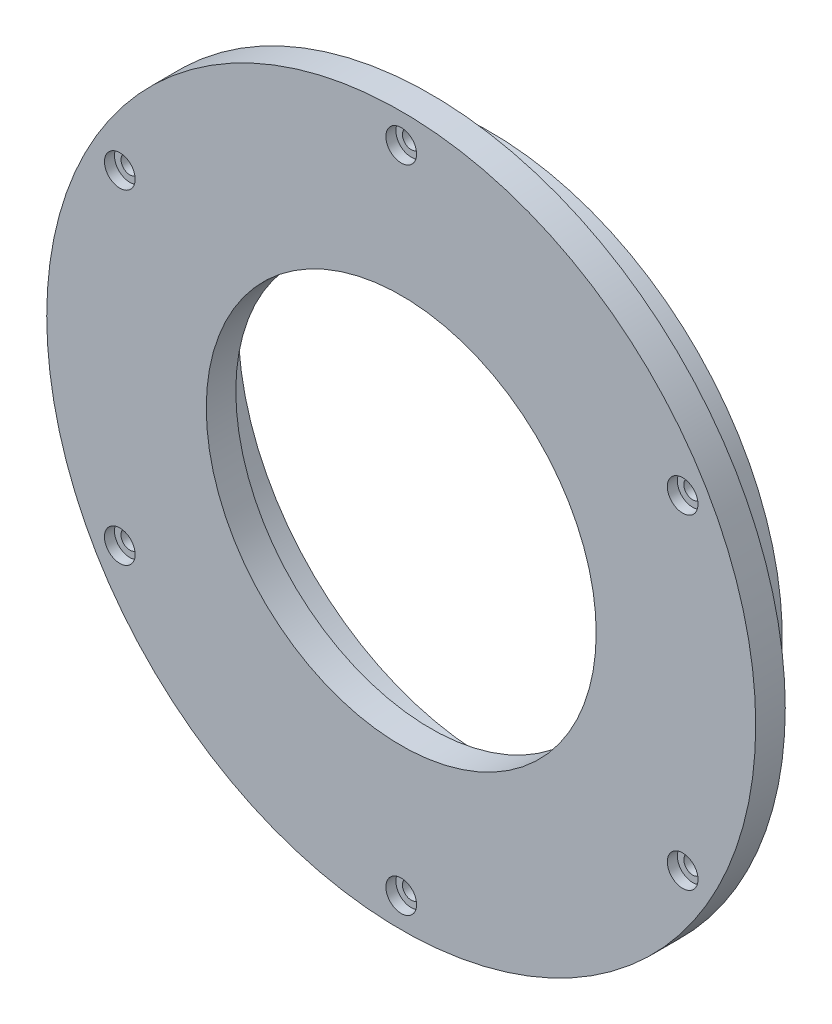
SolidWorks part; units mm, degrees
ref_plane "Front Plane" through (0, 0, 0) normal (0, 0, 1) x (1, 0, 0)
ref_plane "Top Plane" through (0, 0, 0) normal (0, 1, 0) x (1, 0, 0)
ref_plane "Right Plane" through (0, 0, 0) normal (1, 0, 0) x (0, 0, -1)
sketch "Sketch1" plane through (0, 0, 0) normal (0, 0, 1) x (1, 0, 0)
  circle A0 centre (0, 0) radius 60
  circle A1 centre (0, 0) radius 33
  dimension "D1" = 120
  dimension "D2" = 66
extrude "Boss-Extrude1" add sketch "Sketch1" along normal blind 5
sketch "Sketch2" plane through (0, 0, 0) normal (0, 0, -1) x (-1, 0, 0)
  circle A0 centre (0, 0) radius 49.5
  circle A1 centre (0, 0) radius 42.6
  dimension "D1" = 99
  dimension "D2" = 85.2
extrude "Boss-Extrude2" add sketch "Sketch2" along normal blind 10
sketch "Sketch3" plane through (0, 0, -10) normal (0, 0, -1) x (-1, 0, 0)
  circle A0 centre (0, 45) radius 1.7
  circle A1 centre (5.53, 44.6589) radius 1.7
  circle A2 centre (10.9761, 43.6409) radius 1.7
  circle A3 centre (16.2559, 41.9613) radius 1.7
  circle A4 centre (21.2892, 39.6455) radius 1.7
  circle A5 centre (25.9998, 36.7289) radius 1.7
  circle A6 centre (30.3163, 33.2554) radius 1.7
  circle A7 centre (34.1732, 29.2778) radius 1.7
  circle A8 centre (37.5121, 24.8564) radius 1.7
  circle A9 centre (40.2823, 20.0582) radius 1.7
  circle A10 centre (42.4419, 14.956) radius 1.7
  circle A11 centre (43.9582, 9.627) radius 1.7
  circle A12 centre (44.808, 4.1521) radius 1.7
  circle A13 centre (44.9787, -1.3858) radius 1.7
  circle A14 centre (44.4674, -6.9026) radius 1.7
  circle A15 centre (43.2822, -12.3148) radius 1.7
  circle A16 centre (41.4407, -17.5404) radius 1.7
  circle A17 centre (38.9711, -22.5) radius 1.7
  circle A18 centre (35.9108, -27.1186) radius 1.7
  circle A19 centre (32.306, -31.326) radius 1.7
  circle A20 centre (28.2116, -35.0586) radius 1.7
  circle A21 centre (23.6894, -38.2598) radius 1.7
  circle A22 centre (18.8082, -40.8809) radius 1.7
  circle A23 centre (13.6419, -42.8824) radius 1.7
  circle A24 centre (8.2687, -44.2338) radius 1.7
  circle A25 centre (2.7702, -44.9146) radius 1.7
  circle A26 centre (-2.7702, -44.9146) radius 1.7
  circle A27 centre (-8.2687, -44.2338) radius 1.7
  circle A28 centre (-13.6419, -42.8824) radius 1.7
  circle A29 centre (-18.8082, -40.8809) radius 1.7
  circle A30 centre (-23.6894, -38.2598) radius 1.7
  circle A31 centre (-28.2116, -35.0586) radius 1.7
  circle A32 centre (-32.306, -31.326) radius 1.7
  circle A33 centre (-35.9108, -27.1186) radius 1.7
  circle A34 centre (-38.9711, -22.5) radius 1.7
  circle A35 centre (-41.4407, -17.5404) radius 1.7
  circle A36 centre (-43.2822, -12.3148) radius 1.7
  circle A37 centre (-44.4674, -6.9026) radius 1.7
  circle A38 centre (-44.9787, -1.3858) radius 1.7
  circle A39 centre (-44.808, 4.1521) radius 1.7
  circle A40 centre (-43.9582, 9.627) radius 1.7
  circle A41 centre (-42.4419, 14.956) radius 1.7
  circle A42 centre (-40.2823, 20.0582) radius 1.7
  circle A43 centre (-37.5121, 24.8564) radius 1.7
  circle A44 centre (-34.1732, 29.2778) radius 1.7
  circle A45 centre (-30.3163, 33.2554) radius 1.7
  circle A46 centre (-25.9998, 36.7289) radius 1.7
  circle A47 centre (-21.2892, 39.6455) radius 1.7
  circle A48 centre (-16.2559, 41.9613) radius 1.7
  circle A49 centre (-10.9761, 43.6409) radius 1.7
  circle A50 centre (-5.53, 44.6589) radius 1.7
  point P105 (0, 0)
  dimension "D1" = 3.4
  dimension "D2" = 45
  dimension "D3" = 51
extrude "Cut-Extrude1" cut sketch "Sketch3" against normal blind 5
sketch "Sketch5" plane through (0, 0, 5) normal (0, 0, 1) x (1, 0, 0)
  circle A0 centre (0, 55) radius 1.5
  circle A1 centre (47.6314, 27.5) radius 1.5
  circle A2 centre (47.6314, -27.5) radius 1.5
  circle A3 centre (0, -55) radius 1.5
  circle A4 centre (-47.6314, -27.5) radius 1.5
  circle A5 centre (-47.6314, 27.5) radius 1.5
  point P15 (0, 0)
  dimension "D1" = 3
  dimension "D2" = 55
  dimension "D3" = 6
extrude "Cut-Extrude2" cut sketch "Sketch5" against normal blind 5
hole_wizard "CBORE for M5 Hex Socket Thin Head Cap Screw4" positions "3DSketch1" profile "Sketch6" counterbore size "M5" standard "ISO" end condition through all
sketch3d "3DSketch1"
  line L0 (-47.6314, 27.5, 0) -> (-47.6314, 27.5, 5) construction
  line L1 (0, 55, 0) -> (0, 55, 5) construction
  line L2 (47.6314, 27.5, 0) -> (47.6314, 27.5, 5) construction
  line L3 (47.6314, -27.5, 0) -> (47.6314, -27.5, 5) construction
  line L4 (0, -55, 0) -> (0, -55, 5) construction
  line L5 (-47.6314, -27.5, 0) -> (-47.6314, -27.5, 5) construction
  point P0 (-47.6314, 27.5, 5)
  point P4 (0, 55, 5)
  point P8 (47.6314, 27.5, 5)
  point P12 (47.6314, -27.5, 5)
  point P16 (0, -55, 5)
  point P20 (-47.6314, -27.5, 5)
sketch "Sketch6" plane through (-47.6314, 27.5, 5) normal (1, 0, 0) x (0, -1, 0)
  line L0 (0, 0) -> (0, 15)
  line L1 (0, 15) -> (1.5, 15)
  line L3 (1.5, 15) -> (1.5, 1.7)
  line L4 (1.5, 1.7) -> (2.6, 1.7)
  line L5 (2.6, 1.7) -> (2.6, 0)
  line L7 (2.6, 0) -> (0, 0)
  line L11 (0, -6.35) -> (0, 107.95) construction
  dimension "Thru Hole Dia." = 3
  dimension "Thru Hole Depth" = 15
  dimension "C'Bore Dia." = 5.2
  dimension "C'Bore Depth" = 1.7
